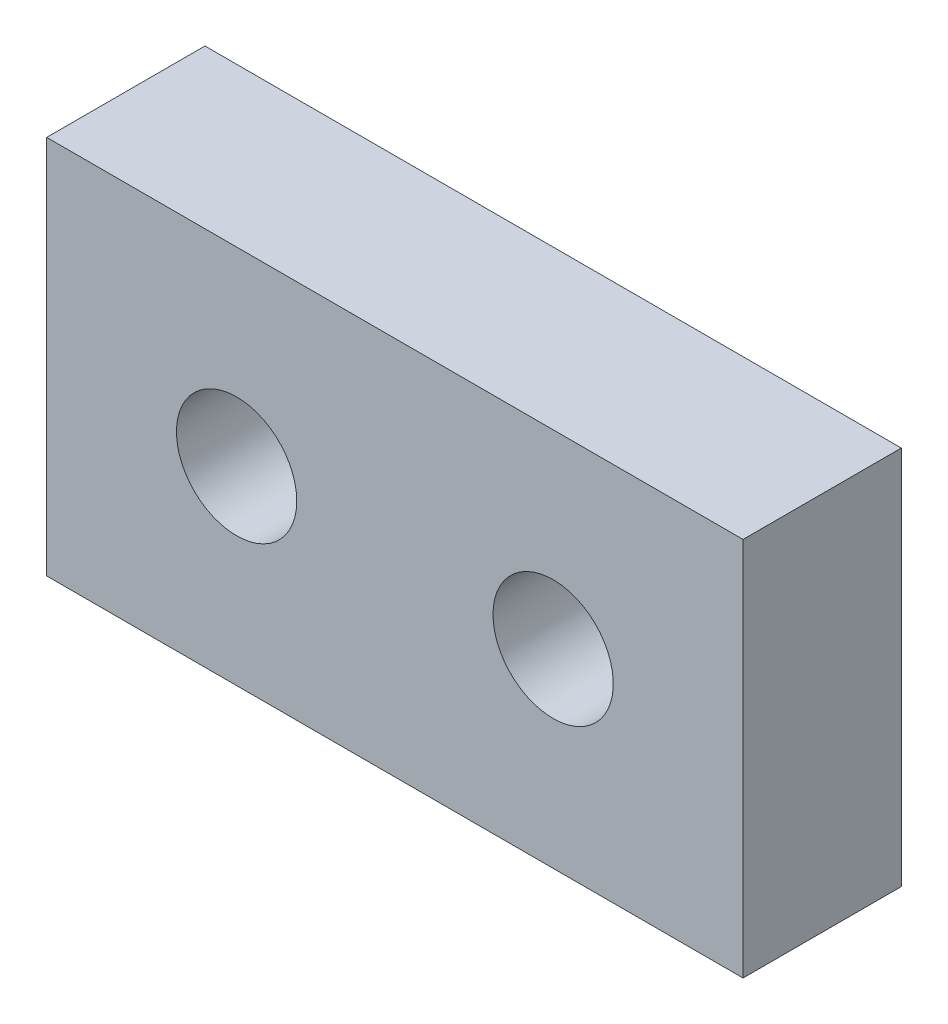
SolidWorks part; units mm, degrees
ref_plane "정면" through (0, 0, 0) normal (0, 0, 1) x (1, 0, 0)
ref_plane "윗면" through (0, 0, 0) normal (0, 1, 0) x (1, 0, 0)
ref_plane "우측면" through (0, 0, 0) normal (1, 0, 0) x (0, 0, -1)
sketch "스케치1" plane through (0, 0, 0) normal (0, 0, 1) x (1, 0, 0)
  line L0 (0, 0) -> (-5, 0) construction
  line L1 (-11, 6) -> (11, 6)
  line L2 (-11, 6) -> (-11, -6)
  line L3 (-11, -6) -> (11, -6)
  line L4 (11, 6) -> (11, -6)
  line L5 (-11, 6) -> (11, -6) construction
  line L6 (-11, -6) -> (11, 6) construction
  line L7 (0, 0) -> (0, 6) construction
  circle A0 centre (-5, 0) radius 1.9
  circle A1 centre (5, 0) radius 1.9
  point P0 (0, 0)
  dimension "D3" = 3.8
  dimension "D1" = 12
  dimension "D2" = 22
  dimension "D4" = 10
extrude "보스-돌출1" add sketch "스케치1" along normal blind 5
